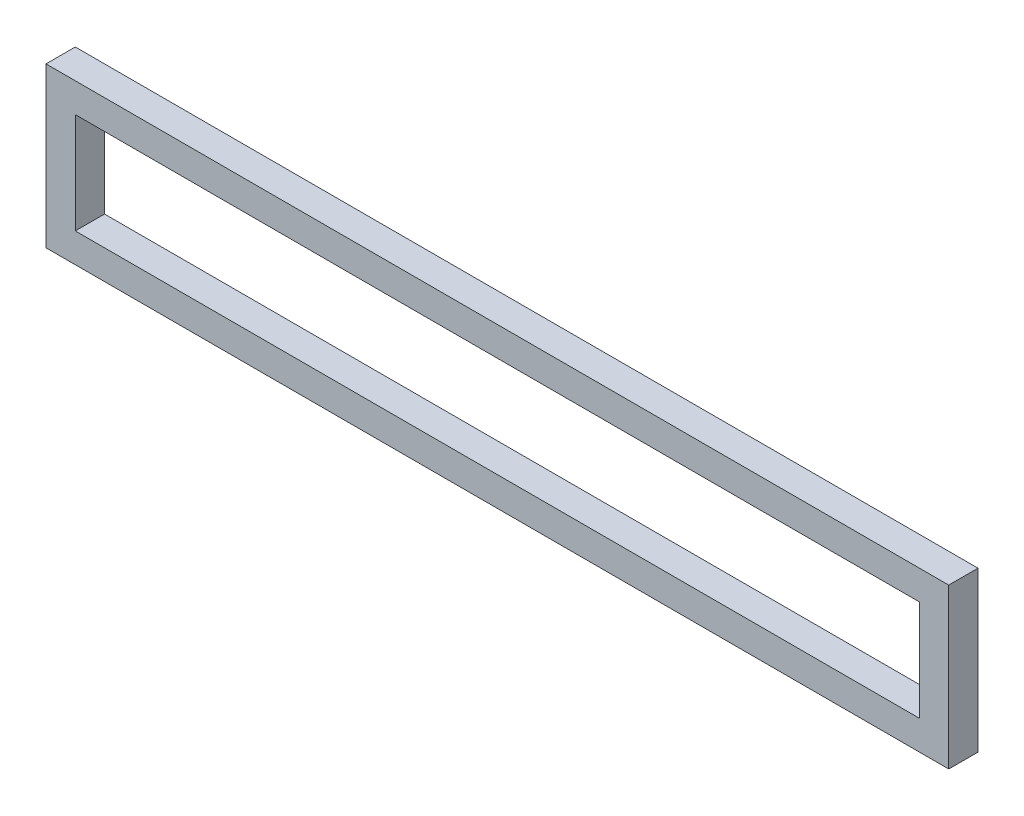
SolidWorks part; units mm, degrees
ref_plane "Front Plane" through (0, 0, 0) normal (0, 0, 1) x (1, 0, 0)
ref_plane "Top Plane" through (0, 0, 0) normal (0, 1, 0) x (1, 0, 0)
ref_plane "Right Plane" through (0, 0, 0) normal (1, 0, 0) x (0, 0, -1)
sketch "Sketch2" plane through (0, 0, 0) normal (0, 0, 1) x (1, 0, 0)
  line L1 (-215.9, 38.1) -> (215.9, 38.1)
  line L2 (-215.9, 38.1) -> (-215.9, -38.1)
  line L3 (-215.9, -38.1) -> (215.9, -38.1)
  line L4 (215.9, 38.1) -> (215.9, -38.1)
  line L5 (-215.9, 38.1) -> (215.9, -38.1) construction
  line L6 (-215.9, -38.1) -> (215.9, 38.1) construction
  point P0 (0, 0)
  dimension "D1" = 431.8
  dimension "D2" = 76.2
extrude "Boss-Extrude3" add sketch "Sketch2" along normal blind 14
sketch "Sketch3" plane through (0, 0, 14) normal (0, 0, 1) x (1, 0, 0)
  line L0 (201.9, 24.1) -> (201.9, -24.1)
  line L2 (-201.9, 24.1) -> (-201.9, -24.1)
  line L6 (201.9, 24.1) -> (-201.9, 24.1)
  line L8 (201.9, -24.1) -> (-201.9, -24.1)
extrude "Cut-Extrude1" cut sketch "Sketch3" against normal blind 14
